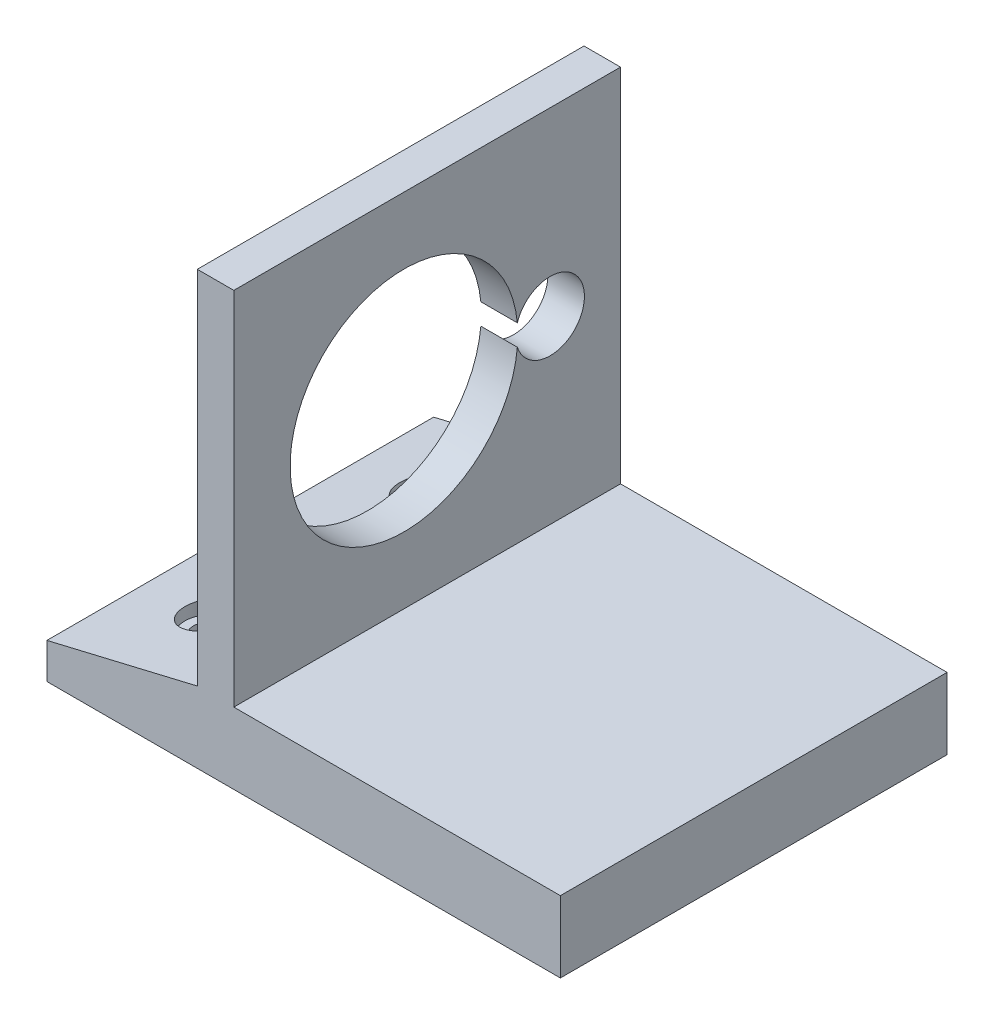
SolidWorks part; units mm, degrees
ref_plane "Plan de face" through (0, 0, 0) normal (0, 0, 1) x (1, 0, 0)
ref_plane "Plan de dessus" through (0, 0, 0) normal (0, 1, 0) x (1, 0, 0)
ref_plane "Plan de droite" through (0, 0, 0) normal (1, 0, 0) x (0, 0, -1)
sketch "Esquisse1" plane through (0, 0, 0) normal (0, 0, 1) x (1, 0, 0)
  line L0 (-38, -554.7609) -> (-38, -596.7609)
  line L1 (-38, -596.7609) -> (0, -596.7609)
  line L2 (0, -596.7609) -> (0, -605.0609)
  line L3 (0, -605.0609) -> (-59.749, -605.0609)
  line L4 (-400, -605.0609) -> (0, -605.0609) construction
  line L5 (-59.749, -605.0609) -> (-59.749, -600.9109)
  line L6 (-59.749, -600.9109) -> (-42.2498, -596.7609)
  line L7 (-42.2498, -596.7609) -> (-42.2498, -554.7609)
  line L8 (-42.2498, -554.7609) -> (-38, -554.7609)
extrude "Boss.-Extru.1" add sketch "Esquisse1" against normal up to surface (45 mm away)
sketch "Esquisse3" plane through (0, -605.0609, 0) normal (0, -1, 0) x (1, 0, 0)
  line L0 (0, 0) -> (-400, 0) construction
  line L1 (0, -45) -> (-400, -45) construction
  circle A0 centre (-50.6835, -35) radius 2
  circle A1 centre (-50.6835, -10) radius 2
  dimension "D3" = 4
  dimension "D1" = 10
  dimension "D2" = 10
extrude "Enlèv. mat.-Extru.2" cut sketch "Esquisse3" against normal through all
sketch "Esquisse4" plane through (0, -554.7609, 0) normal (0, 1, 0) x (1, 0, 0)
  circle A5 centre (-50.6835, 10) radius 3
  circle A6 centre (-50.6835, 10) radius 3
  circle A8 centre (-50.6835, 35) radius 3
  circle A9 centre (-50.6835, 35) radius 3
  dimension "D1" = 1
  dimension "D2" = 1
extrude "Enlèv. mat.-Extru.3" cut sketch "Esquisse4" against normal up to vertex (46.15 mm away)
sketch "Esquisse5" plane through (-42.2498, 0, 0) normal (-1, 0, 0) x (0, 0, 1)
  circle A0 centre (-36.8, -575.7609) radius 4 construction
  arc A1 (-32.993, -574.5333) -> (-32.993, -576.9884) centre (-36.8, -575.7609) ccw
  circle A4 centre (-19.8, -575.7609) radius 13.25
  arc A5 (-32.993, -576.9884) -> (-32.993, -574.5333) centre (-19.8, -575.7609) ccw
  dimension "D1" = 1
extrude "Enlèv. mat.-Extru.4" cut sketch "Esquisse5" against normal through all
